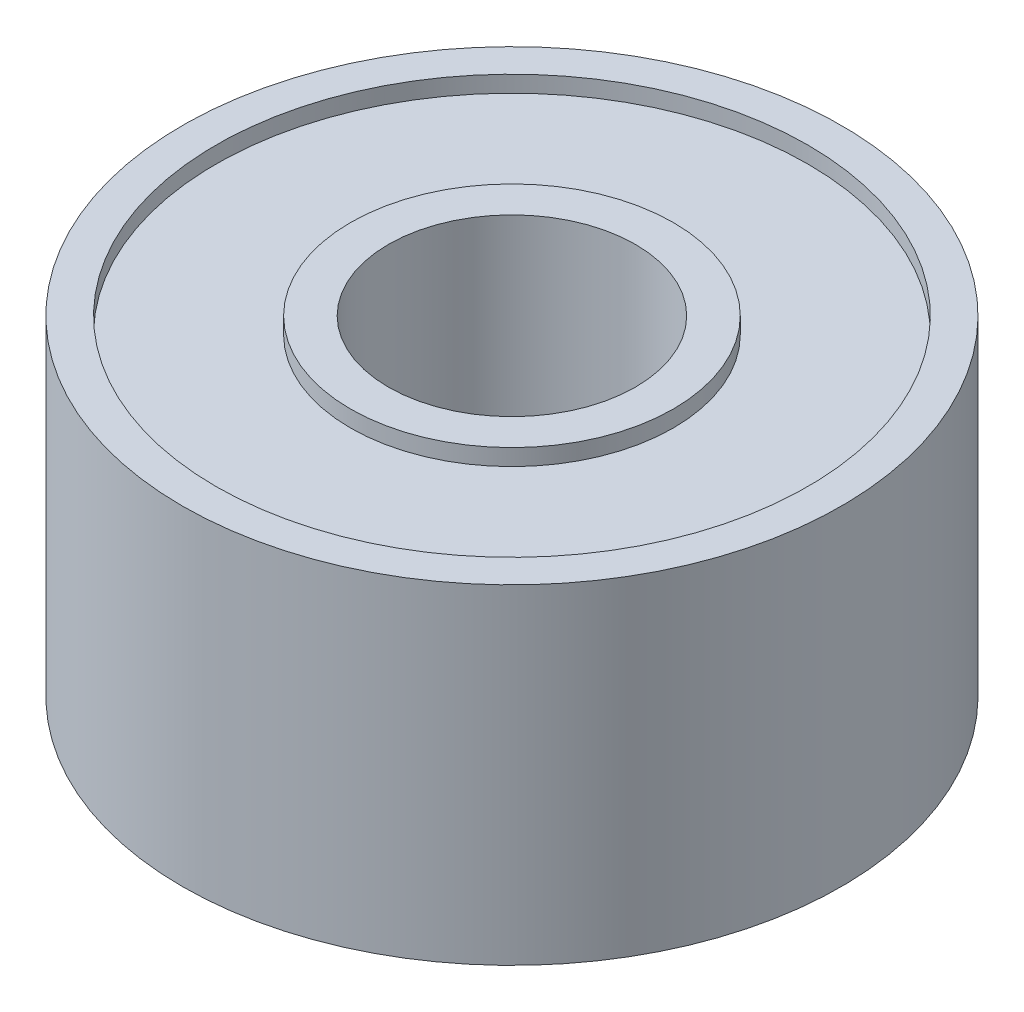
SolidWorks part; units mm, degrees
material "合金钢"
ref_plane "前视基准面" through (0, 0, 0) normal (0, 0, 1) x (1, 0, 0)
ref_plane "上视基准面" through (0, 0, 0) normal (0, 1, 0) x (1, 0, 0)
ref_plane "右视基准面" through (0, 0, 0) normal (1, 0, 0) x (0, 0, -1)
other "质心 (COM)"
sketch "草图1" plane through (0, 0, 0) normal (0, 1, 0) x (1, 0, 0)
  circle A0 centre (0, 0) radius 1.5
  circle A1 centre (0, 0) radius 4
extrude "凸台-拉伸1" add sketch "草图1" along normal blind 4
sketch "草图2" plane through (0, 4, 0) normal (0, 1, 0) x (1, 0, 0)
  circle A0 centre (0, 0) radius 1.9597
  circle A1 centre (0, 0) radius 3.5909
extrude "切除-拉伸1" cut sketch "草图2" against normal blind 0.2
sketch "草图3" plane through (0, 0, 0) normal (0, -1, 0) x (1, 0, 0)
  circle A0 centre (0, 0) radius 1.9434
  circle A1 centre (0, 0) radius 3.5909
  circle A2 centre (0, 0) radius 3.5909
  dimension "D1" = 0
extrude "切除-拉伸2" cut sketch "草图3" against normal blind 0.2
